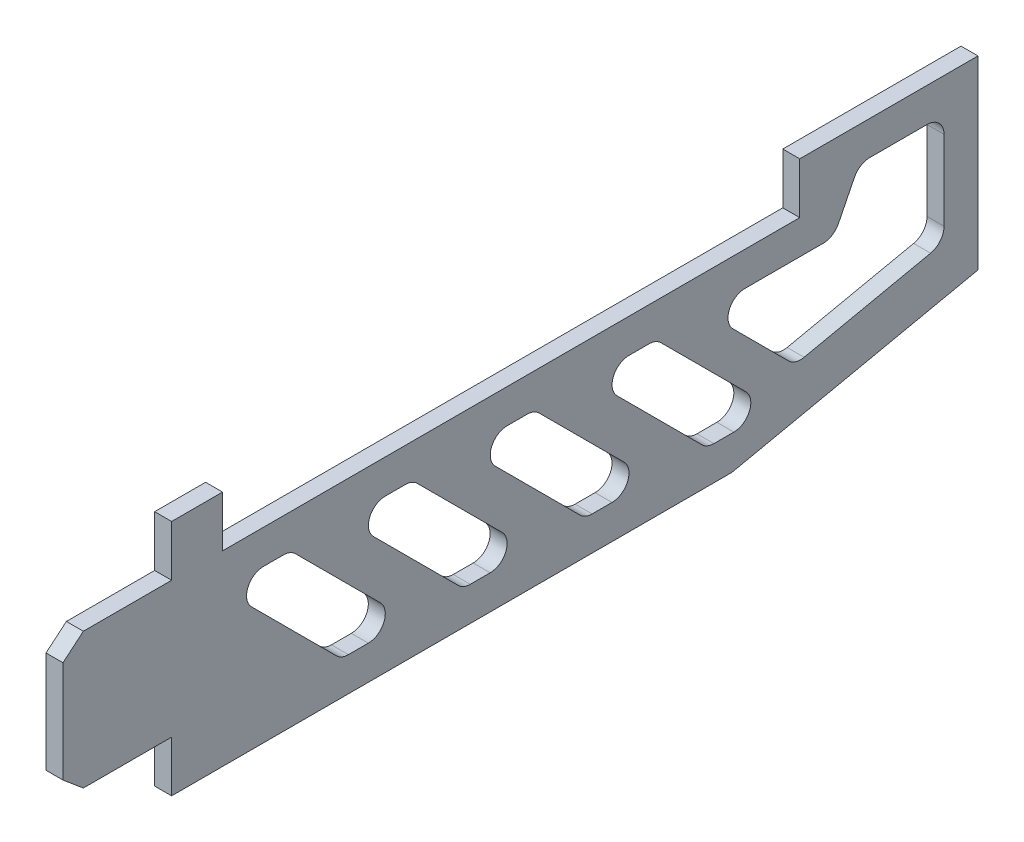
SolidWorks part; units mm, degrees
ref_plane "Ebene vorne" through (0, 0, 0) normal (0, 0, 1) x (1, 0, 0)
ref_plane "Ebene oben" through (0, 0, 0) normal (0, 1, 0) x (1, 0, 0)
ref_plane "Ebene rechts" through (0, 0, 0) normal (1, 0, 0) x (0, 0, -1)
sketch "Skizze1" plane through (0, 0, 0) normal (1, 0, 0) x (0, 0, -1)
  line L1 (0, 0) -> (237.5, 0)
  line L2 (0, 0) -> (0, 70)
  line L3 (0, 70) -> (237.5, 70)
  line L4 (237.5, 0) -> (237.5, 70)
  dimension "D1" = 70
  dimension "D2" = 237.5
extrude "Aufsatz-Linear austragen1" add sketch "Skizze1" along normal blind 5
sketch "Skizze2" plane through (5, 0, 0) normal (1, 0, 0) x (0, 0, -1)
  line L0 (165, 0) -> (237.5, 15.4104)
  line L1 (0, 0) -> (237.5, 0) construction
  line L2 (237.5, 0) -> (237.5, 70) construction
  line L3 (237.5, 15.4104) -> (237.5, 0)
  line L4 (237.5, 0) -> (165, 0)
  dimension "D1" = 12
  dimension "D2" = 165
extrude "Schnitt-Linear austragen1" cut sketch "Skizze2" against normal through all
sketch "Skizze3" plane through (5, 0, 0) normal (1, 0, 0) x (0, 0, -1)
  line L0 (237.5, 70) -> (0, 70) construction
  line L1 (15, 70) -> (185, 70)
  line L2 (15, 70) -> (15, 55)
  line L3 (15, 55) -> (185, 55)
  line L4 (185, 70) -> (185, 55)
  line L5 (0, 70) -> (0, 0) construction
  dimension "D1" = 170
  dimension "D2" = 15
  dimension "D3" = 15
extrude "Schnitt-Linear austragen2" cut sketch "Skizze3" against normal blind 5
sketch "Skizze4" plane through (5, 0, 0) normal (1, 0, 0) x (0, 0, -1)
  line L0 (15, 55) -> (15, 27.5) construction
  line L1 (15, 27.5) -> (15, 0) construction
  line L2 (0, 0) -> (165, 0) construction
  line L3 (15, 27.5) -> (237.5, 27.5) construction
  line L4 (237.5, 15.4104) -> (237.5, 70) construction
  line L5 (15, 45) -> (50, 10)
  line L6 (15, 45) -> (35, 45)
  line L7 (50, 10) -> (70, 10)
  line L8 (35, 45) -> (70, 10)
  line L9 (15, 55) -> (185, 55) construction
  line L10 (50.8845, 27.5) -> (273.3845, 27.5) construction
  line L11 (50.8845, 45) -> (70.8845, 45)
  line L12 (70.8845, 45) -> (105.8845, 10)
  line L13 (85.8845, 10) -> (105.8845, 10)
  line L14 (50.8845, 45) -> (85.8845, 10)
  line L15 (86.769, 27.5) -> (309.269, 27.5) construction
  line L16 (86.769, 45) -> (106.769, 45)
  line L17 (106.769, 45) -> (141.769, 10)
  line L18 (121.769, 10) -> (141.769, 10)
  line L19 (86.769, 45) -> (121.769, 10)
  line L20 (122.6535, 27.5) -> (345.1535, 27.5) construction
  line L21 (122.6535, 45) -> (142.6535, 45)
  line L22 (142.6535, 45) -> (177.6535, 10)
  line L23 (157.6535, 10) -> (177.6535, 10)
  line L24 (122.6535, 45) -> (157.6535, 10)
  line L25 (227.5, 60) -> (227.5, 27.5)
  line L26 (227.5, 27.5) -> (183.6222, 18.1735)
  line L27 (183.6222, 18.1735) -> (156.7957, 45)
  line L28 (156.7957, 45) -> (195, 45)
  line L29 (195, 45) -> (202.5, 60)
  line L30 (202.5, 60) -> (227.5, 60)
  line L32 (237.5, 15.4104) -> (165, 0) construction
  line L33 (237.5, 70) -> (185, 70) construction
  line L34 (185, 55) -> (185, 70) construction
  point P3 (32.5, 27.5)
  dimension "D1" = 10
  dimension "D2" = 45
  dimension "D3" = 20
  dimension "D5" = 10
  dimension "D6" = 10
  dimension "D7" = 10
  dimension "D8" = 10
  dimension "D9" = 25
  dimension "D10" = 10
  dimension "D4" = 4
extrude "Schnitt-Linear austragen3" cut sketch "Skizze4" against normal through all
fillet "Verrundung1" radius 5 22 edges at (2.5, 10, -157.6535) (2.5, 10, -177.6535) (2.5, 45, -142.6535) (2.5, 45, -122.6535) (2.5, 45, -86.769) (2.5, 45, -106.769) (2.5, 10, -141.769) (2.5, 10, -121.769) (2.5, 10, -85.8845) (2.5, 10, -105.8845) (2.5, 45, -70.8845) (2.5, 45, -50.8845) (2.5, 10, -50) (2.5, 10, -70) (2.5, 45, -35) (2.5, 45, -15) (2.5, 18.1735, -183.6222) (2.5, 27.5, -227.5) (2.5, 60, -227.5) (2.5, 45, -195) (2.5, 60, -202.5) (2.5, 45, -156.7957)
sketch "Skizze5" plane through (5, 0, 0) normal (1, 0, 0) x (0, 0, -1)
  line L0 (0, 55) -> (-26, 55)
  line L1 (0, 70) -> (0, 0) construction
  line L2 (-26, 55) -> (-32, 49.9654)
  line L3 (-32, 49.9654) -> (-32, 20.0346)
  line L4 (-32, 35) -> (0, 35) construction
  line L5 (0, 55) -> (0, 15)
  line L6 (-26, 15) -> (-32, 20.0346)
  line L7 (0, 15) -> (-26, 15)
  dimension "D1" = 32
  dimension "D2" = 40
  dimension "D3" = 140
  dimension "D4" = 26
extrude "LascheNase" add sketch "Skizze5" against normal up to surface (5 mm away) up to face at (0, 42.0364, -199.758)
